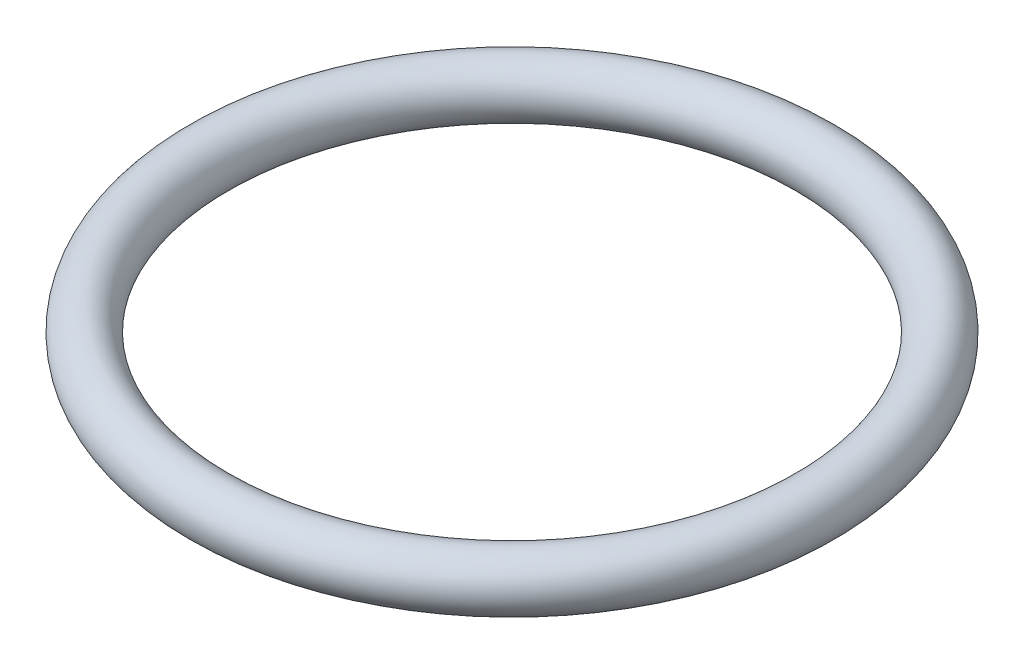
SolidWorks part; units mm, degrees
material "VITON"
ref_plane "Front Plane" through (0, 0, 0) normal (0, 0, 1) x (1, 0, 0)
ref_plane "Top Plane" through (0, 0, 0) normal (0, 1, 0) x (1, 0, 0)
ref_plane "Right Plane" through (0, 0, 0) normal (1, 0, 0) x (0, 0, -1)
sketch "Sketch1" plane through (0, 0, 0) normal (0, 0, 1) x (1, 0, 0)
  line L0 (0, 0) -> (0, 6.5809) construction
  circle A0 centre (-13.97, 0) radius 1.25
  dimension "D1" = 2.5
  dimension "D2" = 13.97
revolve "Revolve1" add sketch "Sketch1" angle 360 about L0
